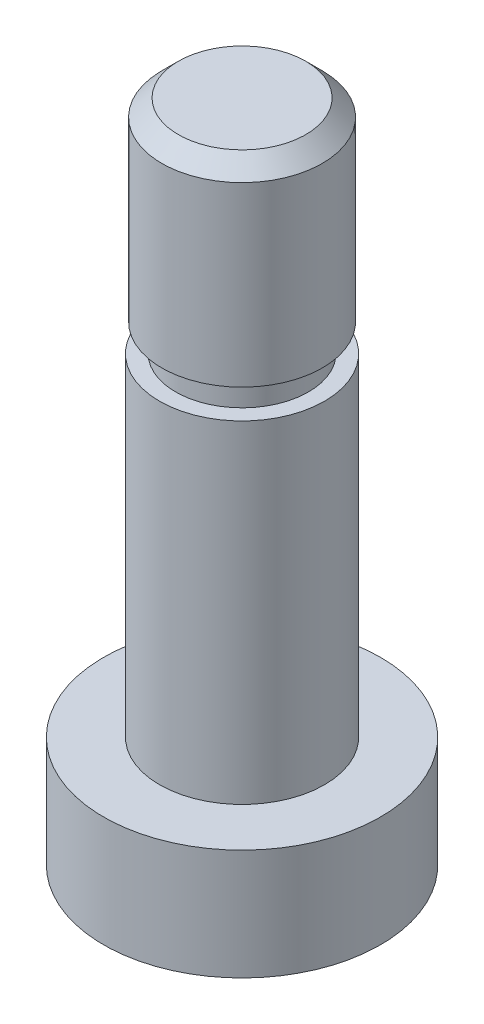
SolidWorks part; units mm, degrees
material "AISI 304"
ref_plane "Plan de face" through (0, 0, 0) normal (0, 0, 1) x (1, 0, 0)
ref_plane "Plan de dessus" through (0, 0, 0) normal (0, 1, 0) x (1, 0, 0)
ref_plane "Plan de droite" through (0, 0, 0) normal (1, 0, 0) x (0, 0, -1)
sketch "Esquisse1" plane through (0, 0, 0) normal (0, 0, 1) x (1, 0, 0)
  line L0 (0, -2) -> (2.5, -2)
  line L1 (2.5, -2) -> (2.5, 0)
  line L2 (2.5, 0) -> (2.3, 0)
  line L3 (2.3, 0) -> (1.49, 0)
  line L4 (1.49, 0) -> (1.49, 6)
  line L5 (1.49, 6) -> (1.2, 6)
  line L6 (1.2, 6) -> (1.2, 6.5)
  line L7 (1.2, 6.5) -> (1.45, 6.5)
  line L8 (1.45, 6.5) -> (1.45, 9.7)
  line L9 (1.45, 9.7) -> (1.15, 10)
  line L10 (1.15, 10) -> (0, 10)
  line L11 (0, 10) -> (0, -2)
  line L12 (0, -4) -> (0, 12) construction
  dimension "D1" = 2
  dimension "D2" = 2.5
  dimension "D3" = 2
  dimension "D4" = 2.5
  dimension "D5" = 1.49
  dimension "D6" = 6
  dimension "D7" = 2.3
  dimension "D8" = 1.45
  dimension "D9" = 9.7
  dimension "D10" = 1.2
  dimension "D11" = 6
  dimension "D12" = 1.2
  dimension "D13" = 6.5
  dimension "D14" = 6.5
  dimension "D15" = 4
  dimension "D16" = 1.15
  dimension "D17" = 10
  dimension "D18" = 10
revolve "Révolution1" add sketch "Esquisse1" angle 360 about L12
sketch "Esquisse2" plane through (0, 0, 0) normal (0, 1, 0) x (1, 0, 0)
  line L1 (1.1547, 0) -> (0.5774, 1)
  line L2 (0.5774, 1) -> (-0.5774, 1)
  line L3 (-0.5774, 1) -> (-1.1547, 0)
  line L4 (-1.1547, 0) -> (-0.5774, -1)
  line L5 (-0.5774, -1) -> (0.5774, -1)
  line L6 (0.5774, -1) -> (1.1547, 0)
  circle A0 centre (0, 0) radius 1.1547 construction
  dimension "D1" = 2.3094
  dimension "D2" = 1.1547
extrude "Enlèv. mat.-Extru.1" cut sketch "Esquisse2" along normal blind 1.3 from offset 2
